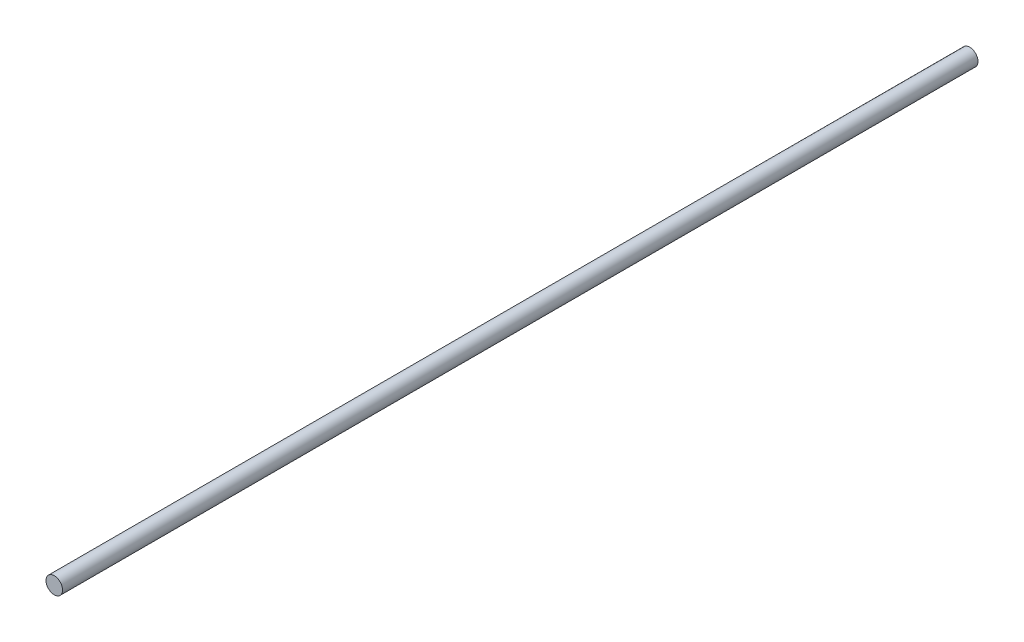
SolidWorks part; units mm, degrees
ref_plane "Front Plane" through (0, 0, 0) normal (0, 0, 1) x (1, 0, 0)
ref_plane "Top Plane" through (0, 0, 0) normal (0, 1, 0) x (1, 0, 0)
ref_plane "Right Plane" through (0, 0, 0) normal (1, 0, 0) x (0, 0, -1)
sketch "Sketch1" plane through (0, 0, 0) normal (0, 0, 1) x (1, 0, 0)
  circle A0 centre (0, 0) radius 50.8
  dimension "D1" = 101.6
extrude "Boss-Extrude1" add sketch "Sketch1" along normal mid plane 5613.4
